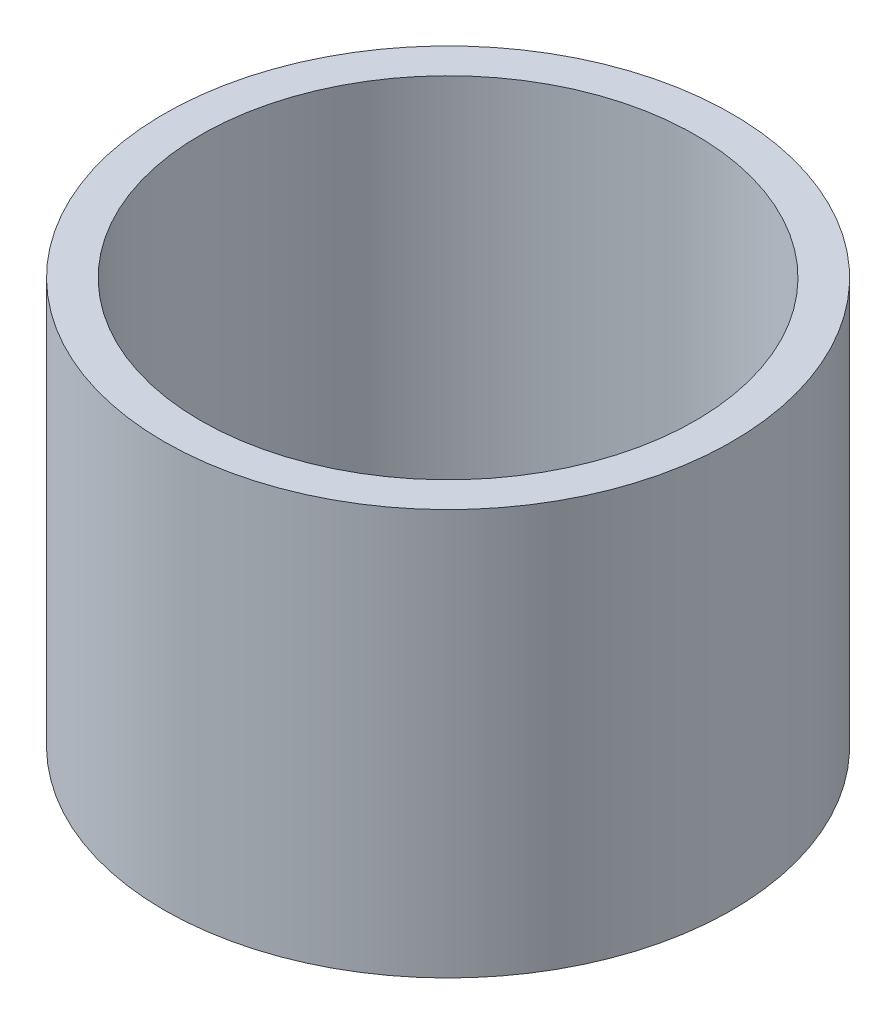
SolidWorks part; units mm, degrees
material "Brass"
ref_plane "Front Plane" through (0, 0, 0) normal (0, 0, 1) x (1, 0, 0)
ref_plane "Top Plane" through (0, 0, 0) normal (0, 1, 0) x (1, 0, 0)
ref_plane "Right Plane" through (0, 0, 0) normal (1, 0, 0) x (0, 0, -1)
sketch "Sketch1" plane through (0, 0, 0) normal (0, 1, 0) x (1, 0, 0)
  circle A0 centre (0, 0) radius 3.05
  circle A1 centre (0, 0) radius 3.5
  dimension "D1" = 7
  dimension "D2" = 0.45
extrude "Boss-Extrude1" add sketch "Sketch1" along normal blind 5
